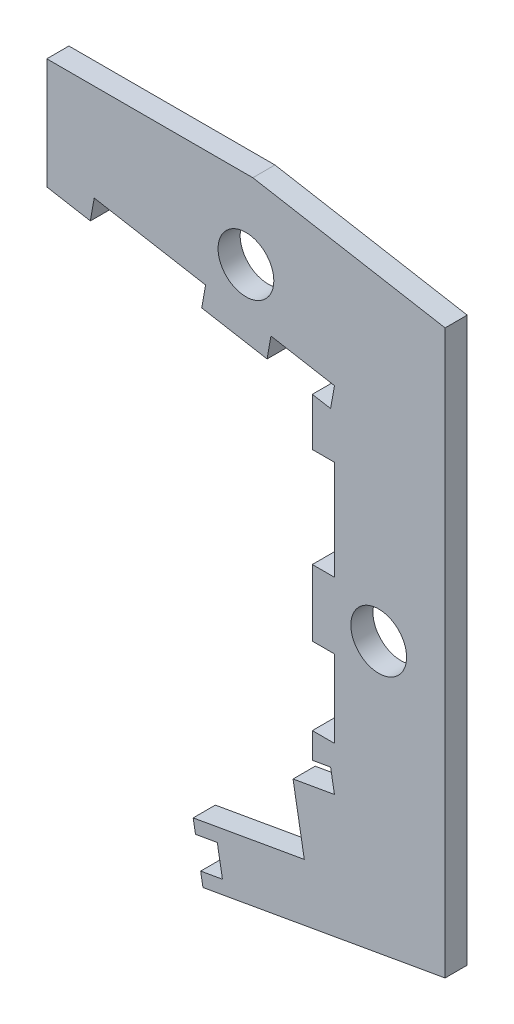
SolidWorks part; units mm, degrees
material "Balsa"
ref_plane "Plan de face" through (0, 0, 0) normal (0, 0, 1) x (1, 0, 0)
ref_plane "Plan de dessus" through (0, 0, 0) normal (0, 1, 0) x (1, 0, 0)
ref_plane "Plan de droite" through (0, 0, 0) normal (1, 0, 0) x (0, 0, -1)
sketch "Esquisse1" plane through (0, 0, 0) normal (0, 0, 1) x (1, 0, 0)
  line L0 (-65, 51.4613) -> (0, 40)
  line L1 (0, 40) -> (0, -40)
  line L2 (-6.8091, -56.1122) -> (-9.3591, -41.6503)
  line L3 (-9.3591, -41.6503) -> (0, -40)
  line L4 (-6.8091, -56.1122) -> (-31.9182, -60.5396)
  line L5 (-29.71, -73.063) -> (25, -63.4162)
  line L6 (25, -63.4162) -> (25, 63.8008)
  line L7 (25, 63.8008) -> (-18.4444, 71.4613)
  line L8 (-65, 71.4613) -> (-65, 51.4613)
  line L9 (7.1417, -5.2313) -> (92.0944, -5.2313) construction
  line L10 (-31.9182, -60.5396) -> (-29.71, -73.063)
  line L11 (-18.4444, 71.4613) -> (-65, 71.4613)
  line L12 (-18.4444, 71.4613) -> (-20, 53.6808) construction
  circle A0 centre (-20, 53.6808) radius 6.3
  circle A1 centre (10, -5) radius 6.3
  point P4 (-29.6197, 71.4613)
  point P19 (-7.4389, 69.5207)
  dimension "D1" = 12.6
  dimension "D15" = 12.6
  dimension "D2" = 10
  dimension "D3" = 20
  dimension "D4" = 80
  dimension "D5" = 65
  dimension "D6" = 100
  dimension "D7" = 100
  dimension "D8" = 85
  dimension "D9" = 35
  dimension "D10" = 90
  dimension "D11" = 9.5035
  dimension "D12" = 14.685
  dimension "D13" = 10
  dimension "D14" = 35
  dimension "D16" = 12.7166
  dimension "D17" = 100
  dimension "D18" = 100
  dimension "D19" = 20
extrude "Boss.-Extru.1" add sketch "Esquisse1" along normal blind 5
sketch "Esquisse2" plane through (0, 0, 0) normal (0, 0, -1) x (-1, 0, 0)
  line L0 (31.3966, -63.498) -> (30.231, -70.1086)
  line L1 (31.3966, -63.498) -> (26.4726, -62.6297)
  line L2 (30.231, -70.1086) -> (25.3069, -69.2404)
  line L3 (26.4726, -62.6297) -> (25.3069, -69.2404)
  line L11 (31.9182, -60.5396) -> (29.71, -73.063) construction
  line L12 (6.8091, -56.1122) -> (31.9182, -60.5396) construction
  dimension "D2" = 5
  dimension "D3" = 3.004
  dimension "D4" = 3
extrude "Enlèv. mat.-Extru.1" cut sketch "Esquisse2" against normal blind 5
sketch "Esquisse3" plane through (0, 0, 0) normal (0, 0, 1) x (1, 0, 0)
  line L0 (0, -40) -> (0, -30)
  line L1 (0, 40) -> (0, -40) construction
  line L2 (0, -40) -> (-9.3591, -41.6503) construction
  line L3 (0, -30) -> (-5, -30)
  line L4 (-5, -30) -> (-5, -35.8045)
  line L5 (-5, -35.8045) -> (-0.8682, -35.076)
  line L6 (-0.8682, -35.076) -> (0, -40)
  line L7 (0, 0) -> (-23.4139, 0) construction
  line L8 (0, 2.5) -> (-5, 2.5)
  line L9 (0, 2.5) -> (0, -12.5)
  line L10 (0, -12.5) -> (-5, -12.5)
  line L11 (-5, 2.5) -> (-5, -12.5)
  line L12 (0, 40) -> (0, -40) construction
  line L13 (-0.8682, 35.076) -> (0, 40)
  line L14 (-5, 35.8045) -> (-0.8682, 35.076)
  line L15 (-5, 25) -> (-5, 35.8045)
  line L16 (0, 25) -> (-5, 25)
  line L17 (0, 40) -> (0, 25)
  line L18 (-29.1225, 45.1351) -> (-14.3504, 42.5304)
  line L19 (-65, 51.4613) -> (0, 40) construction
  line L20 (-14.3504, 42.5304) -> (-15.2187, 37.6063)
  line L21 (-15.2187, 37.6063) -> (-29.9908, 40.2111)
  line L22 (-29.9908, 40.2111) -> (-29.1225, 45.1351)
  line L23 (-65, 51.4613) -> (-65, 46.3841)
  line L24 (-65, 46.3841) -> (-55.1519, 44.6476)
  line L25 (-55.1519, 44.6476) -> (-54.2837, 49.5717)
  line L26 (-54.2837, 49.5717) -> (-65, 51.4613)
  line L27 (-65, 71.4613) -> (-65, 51.4613) construction
  circle A0 centre (10, -5) radius 6.3 construction
  circle A1 centre (-20, 53.6808) radius 6.3 construction
  dimension "D1" = 10
  dimension "D2" = 5
  dimension "D3" = 5
  dimension "D4" = 10
  dimension "D5" = 5
  dimension "D6" = 7.5
  dimension "D7" = 15
  dimension "D8" = 15
  dimension "D9" = 5
  dimension "D10" = 15
  dimension "D11" = 7.5
  dimension "D12" = 5
  dimension "D13" = 10
extrude "Boss.-Extru.3" add sketch "Esquisse3" along normal blind 5
